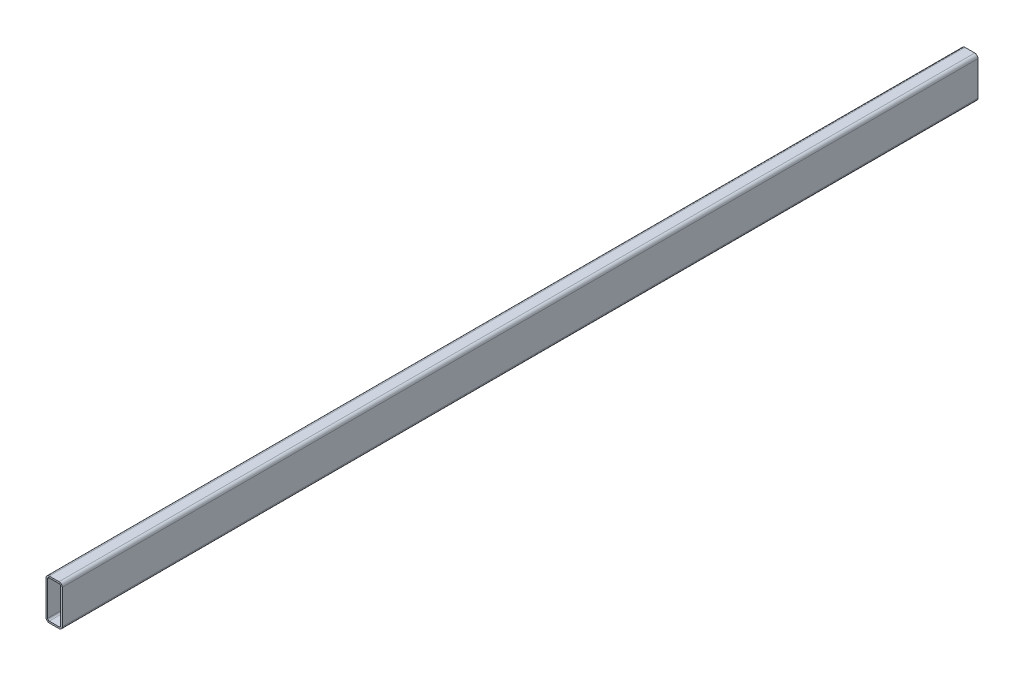
SolidWorks part; units mm, degrees
material "Plain Carbon Steel"
ref_plane "Front Plane" through (0, 0, 0) normal (0, 0, 1) x (1, 0, 0)
ref_plane "Top Plane" through (0, 0, 0) normal (0, 1, 0) x (1, 0, 0)
ref_plane "Right Plane" through (0, 0, 0) normal (1, 0, 0) x (0, 0, -1)
sketch "Sketch1" plane through (0, 0, 0) normal (0, 0, 1) x (1, 0, 0)
  line L0 (0, 73.7462) -> (0, -75.1353) construction
  line L1 (-89.5999, 0) -> (92.4117, 0) construction
  line L2 (-10, 0) -> (-10, -21)
  line L3 (-6, -25) -> (0, -25)
  line L4 (-8, 0) -> (-8, -21)
  line L5 (-6, -23) -> (0, -23)
  line L6 (6, -23) -> (0, -23)
  line L7 (8, 0) -> (8, -21)
  line L8 (-6, 25) -> (6, 25)
  line L9 (-10, 0) -> (-10, 21)
  line L10 (8, 0) -> (8, 21)
  line L11 (-6, 23) -> (6, 23)
  line L12 (-8, 0) -> (-8, 21)
  line L13 (6, -25) -> (0, -25)
  line L14 (10, 0) -> (10, -21)
  line L15 (10, 0) -> (10, 21)
  arc A0 (-10, -21) -> (-6, -25) centre (-6, -21) ccw
  arc A1 (-8, -21) -> (-6, -23) centre (-6, -21) ccw
  arc A2 (8, -21) -> (6, -23) centre (6, -21) cw
  arc A3 (-10, 21) -> (-6, 25) centre (-6, 21) cw
  arc A4 (8, 21) -> (6, 23) centre (6, 21) ccw
  arc A5 (-8, 21) -> (-6, 23) centre (-6, 21) cw
  arc A6 (10, -21) -> (6, -25) centre (6, -21) cw
  arc A7 (10, 21) -> (6, 25) centre (6, 21) ccw
  point P10 (-10, -25)
  point P31 (0, 57.5)
  point P37 (0, 25)
  dimension "D3" = 4
  dimension "D1" = 25
  dimension "D2" = 10
  dimension "D4" = 2
extrude "Boss-Extrude1" add sketch "Sketch1" along normal mid plane 1125
